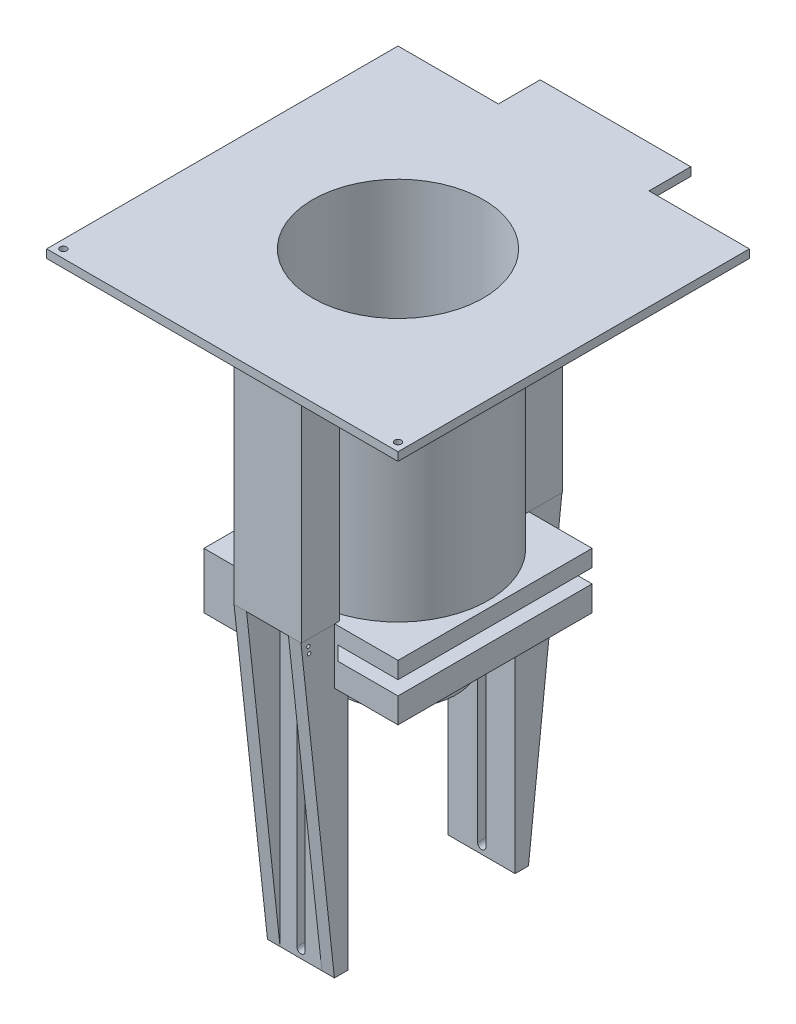
SolidWorks part; units mm, degrees
ref_plane "Front Plane" through (0, 0, 0) normal (0, 0, 1) x (1, 0, 0)
ref_plane "Top Plane" through (0, 0, 0) normal (0, 1, 0) x (1, 0, 0)
ref_plane "Right Plane" through (0, 0, 0) normal (1, 0, 0) x (0, 0, -1)
sketch "Sketch4" plane through (0, 0, 0) normal (0, 1, 0) x (1, 0, 0)
  line L1 (-58, 58) -> (58, 58)
  line L2 (-58, 58) -> (-58, -58)
  line L3 (-58, -58) -> (58, -58)
  line L4 (58, 58) -> (58, -58)
  dimension "D1" = 58
  dimension "D2" = 58
  dimension "D3" = 58
  dimension "D4" = 58
extrude "Boss-Extrude1" add sketch "Sketch4" along normal blind 10
sketch "Sketch6" plane through (0, 10, 0) normal (0, 1, 0) x (1, 0, 0)
  circle A0 centre (0, 0) radius 33.5
  dimension "D1" = 67
extrude "Cut-Extrude1" cut sketch "Sketch6" against normal through all
sketch "Sketch8" plane through (0, 0, 0) normal (0, -1, 0) x (1, 0, 0)
  line L7 (-58, 58) -> (-58, -58)
  line L8 (22, -58) -> (-58, -58)
  line L9 (58, -58) -> (-58, -58) construction
  line L10 (-58, 58) -> (22, 58)
  line L11 (-58, 58) -> (58, 58) construction
  arc A1 (22, 58) -> (22, -58) centre (22, 0) ccw
  dimension "D3" = 58
  dimension "D1" = 80
  dimension "D2" = 116
extrude "Boss-Extrude3" add sketch "Sketch8" along normal blind 8.4
sketch "Sketch10" plane through (0, -8.4, 0) normal (0, -1, 0) x (1, 0, 0)
  line L1 (-58, 58) -> (58, 58)
  line L2 (-58, 58) -> (-58, -58)
  line L3 (-58, -58) -> (58, -58)
  line L4 (58, 58) -> (58, -58)
extrude "Boss-Extrude5" add sketch "Sketch10" along normal blind 15
sketch "Sketch11" plane through (0, -23.4, 0) normal (0, -1, 0) x (1, 0, 0)
  circle A0 centre (39, 0) radius 4
  dimension "D1" = 8
  dimension "D2" = 39
extrude "positioning hole" cut sketch "Sketch11" against normal blind 28
sketch "Sketch23" plane through (0, -23.4, 0) normal (0, -1, 0) x (1, 0, 0)
  circle A0 centre (38.947, 20) radius 4
  circle A1 centre (39, 0) radius 4 construction
  dimension "D2" = 8
  dimension "D1" = 20
extrude "snapping hole" cut sketch "Sketch23" against normal blind 28
sketch "Sketch13" plane through (0, -23.4, 0) normal (0, -1, 0) x (1, 0, 0)
  circle A0 centre (0, 0) radius 34.75
  circle A1 centre (0, 0) radius 33.5
  dimension "D1" = 69.5
  dimension "D2" = 67
extrude "Boss-Extrude6" add sketch "Sketch13" along normal blind 25
sketch "Sketch24" plane through (0, -23.4, 0) normal (0, -1, 0) x (1, 0, 0)
  line L0 (58, 58) -> (-58, 58) construction
  line L1 (-20, 58) -> (20, 58)
  line L2 (-20, 58) -> (-20, 50)
  line L3 (-20, 50) -> (20, 50)
  line L4 (20, 58) -> (20, 50)
  line L5 (-58, -58) -> (58, -58) construction
  line L6 (-20, -58) -> (20, -58)
  line L7 (-20, -58) -> (-20, -50)
  line L8 (-20, -50) -> (20, -50)
  line L9 (20, -58) -> (20, -50)
  dimension "D1" = 100
  dimension "D2" = 20
  dimension "D3" = 20
  dimension "D4" = 8
  dimension "D5" = 20
  dimension "D6" = 20
extrude "Boss-Extrude7" add sketch "Sketch24" along normal blind 150
sketch "Sketch28" plane through (-20, 0, 0) normal (-1, 0, 0) x (0, 0, 1)
  line L0 (-58, -173.4) -> (-58, 10)
  line L1 (-58, 10) -> (-78, 10)
  line L2 (-78, 10) -> (-58, -173.4)
  line L3 (58, 10) -> (58, -173.4)
  line L4 (58, -173.4) -> (78, 10)
  line L5 (78, 10) -> (58, 10)
  dimension "D1" = 20
  dimension "D2" = 20
extrude "Boss-Extrude9" add sketch "Sketch28" against normal blind 40
sketch "Sketch31" plane through (0, 0, -58) normal (0, 0, -1) x (-1, 0, 0)
  line L0 (2.5, -28.4) -> (2.5, -168.4)
  line L1 (-2.5, -28.4) -> (-2.5, -168.4)
  line L2 (20, -173.4) -> (-20, -173.4) construction
  line L3 (58, -23.4) -> (20, -23.4) construction
  arc A0 (-2.5, -168.4) -> (2.5, -168.4) centre (0, -168.4) ccw
  arc A1 (-2.5, -28.4) -> (2.5, -28.4) centre (0, -28.4) cw
  dimension "D1" = 5
  dimension "D2" = 2.5
  dimension "D3" = 2.5
  dimension "D4" = 5
extrude "Cut-Extrude6" cut sketch "Sketch31" against normal up to next (8 mm away) and the other way through all
sketch "Sketch34" plane through (0, 0, 50) normal (0, 0, -1) x (-1, 0, 0)
  line L0 (-2.5, -28.4) -> (-2.5, -168.4)
  line L1 (2.5, -28.4) -> (2.5, -168.4)
  arc A0 (-2.5, -168.4) -> (2.5, -168.4) centre (0, -168.4) ccw
  arc A1 (-2.5, -28.4) -> (2.5, -28.4) centre (0, -28.4) cw
extrude "Cut-Extrude7" cut sketch "Sketch34" against normal up to next
sketch "Sketch37" plane through (0, 10, 0) normal (0, 1, 0) x (1, 0, 0)
  line L0 (0, 0) -> (-80.0321, 0) construction
  line L1 (-12.5, 58) -> (12.5, 58)
  line L2 (-12.5, 58) -> (-12.5, 78)
  line L3 (-12.5, 78) -> (12.5, 78)
  line L4 (12.5, 58) -> (12.5, 78)
  line L5 (-80.0321, 0) -> (99.0974, 0) construction
  line L6 (12.5, -58) -> (12.5, -78)
  line L7 (-12.5, -78) -> (12.5, -78)
  line L8 (-12.5, -58) -> (-12.5, -78)
  line L9 (-12.5, -58) -> (12.5, -58)
  line L10 (58, 58) -> (20, 58) construction
  dimension "D1" = 20
  dimension "D2" = 25
  dimension "D3" = 12.5
extrude "Cut-Extrude9" cut sketch "Sketch37" against normal up to next
sketch "Sketch12" plane through (0, -23.4, 0) normal (0, -1, 0) x (1, 0, 0)
  circle A0 centre (0, 0) radius 33.5
  dimension "D1" = 67
extrude "main hole" cut sketch "Sketch12" against normal through all
sketch "Sketch42" plane through (0, 10, 0) normal (0, 1, 0) x (1, 0, 0)
  circle A0 centre (0, 0) radius 54
  circle A1 centre (0, 0) radius 51
  dimension "D1" = 102
  dimension "D2" = 108
extrude "Boss-Extrude12" add sketch "Sketch42" along normal blind 150
chamfer "Chamfer3" distance 5 angle 45 1 edges at (0, 10, 33.5)
sketch "Sketch44" plane through (0, 10, 0) normal (0, 1, 0) x (1, 0, 0)
  line L1 (-20, 78) -> (20.1827, 78)
  line L2 (-20, 78) -> (-20, 55)
  line L3 (-20, 55) -> (20.1827, 55)
  line L4 (20.1827, 78) -> (20.1827, 55)
  line L5 (-20, -78) -> (20.1827, -78)
  line L6 (-20, -78) -> (-20, -55)
  line L7 (-20, -55) -> (20.1827, -55)
  line L8 (20.1827, -78) -> (20.1827, -55)
  dimension "D1" = 23
  dimension "D2" = 23
extrude "Boss-Extrude15" add sketch "Sketch44" along normal blind 150
sketch "Sketch41" plane through (0, 160, 0) normal (0, 1, 0) x (1, 0, 0)
  line L0 (45, 105) -> (105, 105)
  line L1 (-105, 105) -> (-45, 105)
  line L2 (-105, 105) -> (-105, -105)
  line L3 (-105, -105) -> (105, -105)
  line L4 (105, 105) -> (105, -105)
  line L6 (-45, 105) -> (-45, 130)
  line L7 (-45, 130) -> (45, 130)
  line L8 (45, 105) -> (45, 130)
  circle A0 centre (-100, -100) radius 2
  circle A1 centre (100, -100) radius 2
  dimension "D8" = 4
  dimension "D13" = 4
  dimension "D1" = 210
  dimension "D2" = 210
  dimension "D3" = 105
  dimension "D4" = 105
  dimension "D5" = 90
  dimension "D6" = 25
  dimension "D7" = 60
  dimension "D9" = 5
  dimension "D10" = 5
  dimension "D11" = 5
  dimension "D12" = 5
extrude "Boss-Extrude11" add sketch "Sketch41" along normal blind 5
sketch "Sketch45" plane through (0, 165, 0) normal (0, 1, 0) x (1, 0, 0)
  circle A0 centre (0, 0) radius 51
  dimension "D1" = 102
extrude "Cut-Extrude12" cut sketch "Sketch45" against normal blind 150
sketch "Sketch46" plane through (20, 0, 0) normal (1, 0, 0) x (0, 0, -1)
  line L0 (-78, 10) -> (-58, 10) construction
  line L1 (-78, 10) -> (-58, 10) construction
  line L2 (-58, -173.4) -> (-78, 10) construction
  circle A0 centre (-73.5401, 6) radius 1
  circle A1 centre (-73.1039, 2) radius 1
  dimension "D1" = 2
  dimension "D2" = 2
  dimension "D3" = 4
  dimension "D4" = 8
  dimension "D5" = 4
  dimension "D6" = 4
extrude "Cut-Extrude13" cut sketch "Sketch46" against normal blind 25
